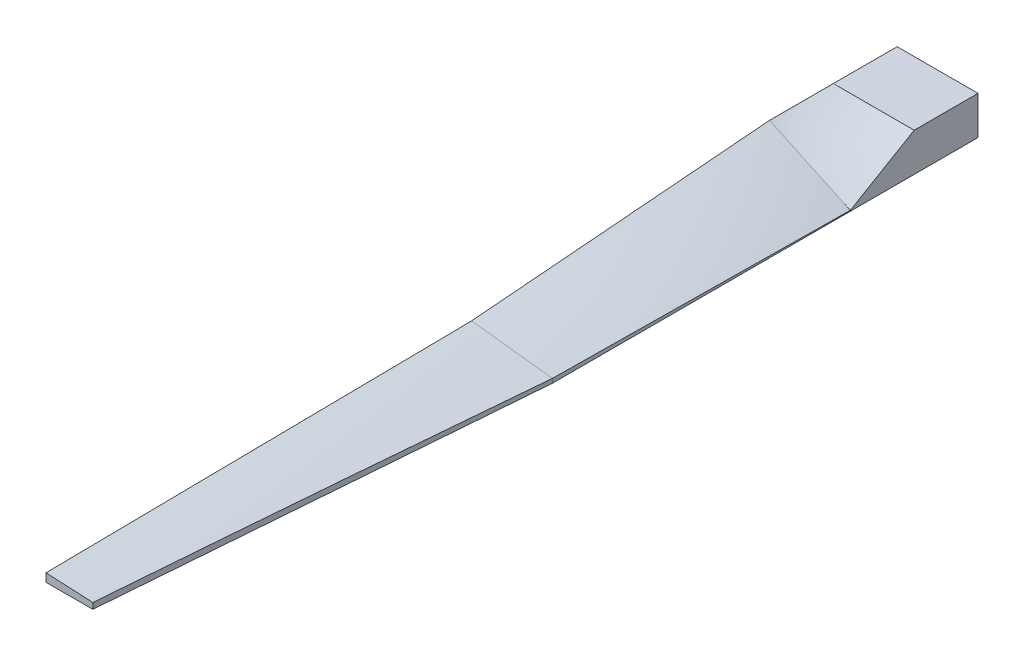
SolidWorks part; units mm, degrees
ref_plane "Front Plane" through (0, 0, 0) normal (0, 0, 1) x (1, 0, 0)
ref_plane "Top Plane" through (0, 0, 0) normal (0, 1, 0) x (1, 0, 0)
ref_plane "Right Plane" through (0, 0, 0) normal (1, 0, 0) x (0, 0, -1)
sketch "Sketch1" plane through (0, 0, 0) normal (0, 0, 1) x (1, 0, 0)
  line L1 (0, 0) -> (95, 0)
  line L2 (0, 0) -> (0, 45)
  line L3 (0, 45) -> (95, 45)
  line L4 (95, 0) -> (95, 45)
  dimension "D1" = 95
  dimension "D2" = 45
ref_plane "Plane1" through (0, 0, 75) normal (0, 0, 1) x (1, 0, 0)
sketch "Sketch2" plane through (0, 0, 75) normal (0, 0, 1) x (1, 0, 0)
  line L1 (0, 0) -> (95, 0)
  line L2 (0, 0) -> (0, 45)
  line L3 (0, 45) -> (95, 45)
  line L4 (95, 0) -> (95, 45)
ref_plane "Plane2" through (0, 0, 150) normal (0, 0, 1) x (1, 0, 0)
sketch "Sketch3" plane through (0, 0, 150) normal (0, 0, 1) x (1, 0, 0)
  line L0 (0, 0) -> (0, 45)
  line L2 (95, 0) -> (0, 0)
  line L3 (0, 45) -> (95, 1)
  line L4 (95, 0) -> (95, 45) construction
  line L5 (95, 1) -> (95, 0)
  dimension "D1" = 1
ref_plane "Plane3" through (0, 0, 500) normal (0, 0, 1) x (1, 0, 0)
sketch "Sketch4" plane through (0, 0, 500) normal (0, 0, 1) x (1, 0, 0)
  line L0 (0, 0) -> (0, 16)
  line L1 (0, 0) -> (0, 45) construction
  line L3 (95, 0) -> (0, 0)
  line L4 (0, 16) -> (95, 5)
  line L5 (95, 0) -> (95, 45) construction
  line L6 (95, 5) -> (95, 0)
  dimension "D1" = 16
  dimension "D2" = 5
ref_plane "Plane4" through (0, 0, 1000) normal (0, 0, 1) x (1, 0, 0)
sketch "Sketch6" plane through (0, 0, 1000) normal (0, 0, 1) x (1, 0, 0)
  line L0 (0, 0) -> (0, 9.6694)
  line L1 (0, 0) -> (0, 45) construction
  line L2 (0, 9.6694) -> (95, 5)
  line L3 (95, 5) -> (95, 0)
  line L4 (95, 0) -> (0, 0)
loft "Loft3" add profiles "Sketch1", "Sketch2"
loft "Loft4" add profiles "Sketch3" section face at (47.5, 22.5, 75) section "Sketch3"
loft "Loft5" add profiles "Sketch4" section face at (47.5, 11.5, 150) section "Sketch4"
loft "Loft6" add profiles "Sketch6" section face at (47.5, 5.25, 500) section "Sketch6"
sketch "Sketch7" plane through (0, 0, 0) normal (0, 1, 0) x (1, 0, 0)
  line L0 (55, -1000) -> (95, -500)
  line L1 (-24.7501, -1000) -> (24.7501, -1000) construction
  line L2 (-24.7501, -500) -> (24.7501, -500) construction
  line L3 (95, -150) -> (95, -500) construction
  line L4 (95, -500) -> (95, -1000)
  line L5 (95, -500) -> (95, -1000) construction
  line L6 (95, -1000) -> (55, -1000)
  line L7 (0, -500) -> (0, -1000) construction
  point P11 (0, 0)
  dimension "D1" = 55
extrude "Cut-Extrude2" cut sketch "Sketch7" against normal through all both and the other way through all
